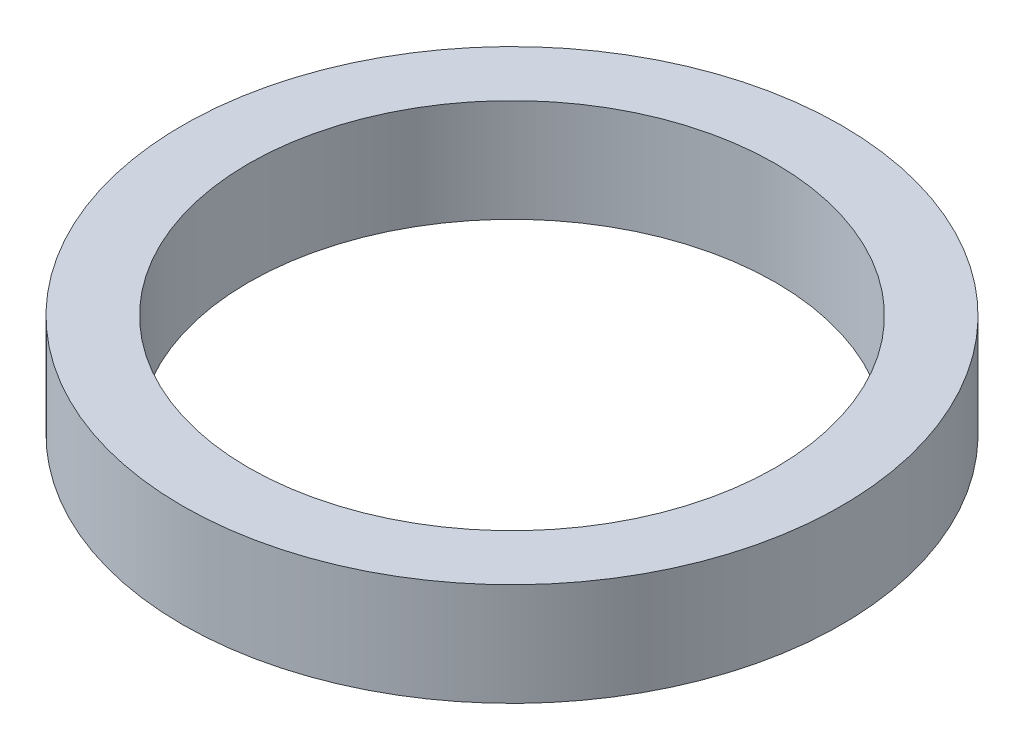
SolidWorks part; units mm, degrees
ref_plane "Alzado" through (0, 0, 0) normal (0, 0, 1) x (1, 0, 0)
ref_plane "Planta" through (0, 0, 0) normal (0, 1, 0) x (1, 0, 0)
ref_plane "Vista lateral" through (0, 0, 0) normal (1, 0, 0) x (0, 0, -1)
sketch "Croquis1" plane through (0, 0, 0) normal (0, 1, 0) x (1, 0, 0)
  circle A0 centre (0, 0) radius 10.25
  circle A1 centre (0, 0) radius 12.825
  dimension "D1" = 25.65
  dimension "D2" = 20.5
extrude "Saliente-Extruir1" add sketch "Croquis1" along normal blind 4
